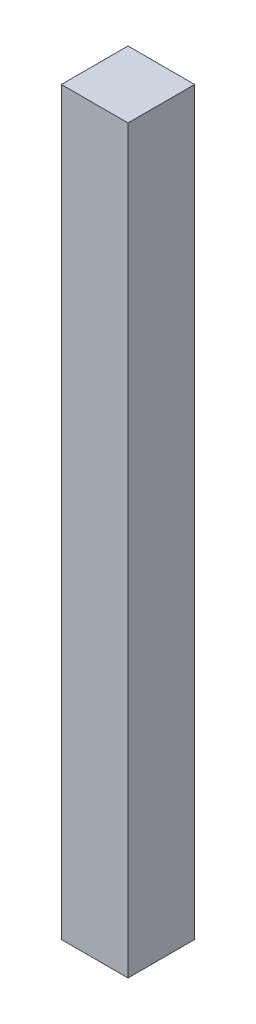
SolidWorks part; units mm, degrees
ref_plane "Front Plane" through (0, 0, 0) normal (0, 0, 1) x (1, 0, 0)
ref_plane "Top Plane" through (0, 0, 0) normal (0, 1, 0) x (1, 0, 0)
ref_plane "Right Plane" through (0, 0, 0) normal (1, 0, 0) x (0, 0, -1)
other "Configuration Table"
sketch "Sketch1" plane through (0, 0, 0) normal (0, 0, 1) x (1, 0, 0)
  line L1 (45, 230) -> (63, 230)
  line L2 (45, 230) -> (45, 430)
  line L3 (45, 430) -> (63, 430)
  line L4 (63, 230) -> (63, 430)
extrude "TOPPING_klape_alt2_gazli_amortisor_1_1" add sketch "Sketch1" along normal blind 18 from offset 8 separate body
